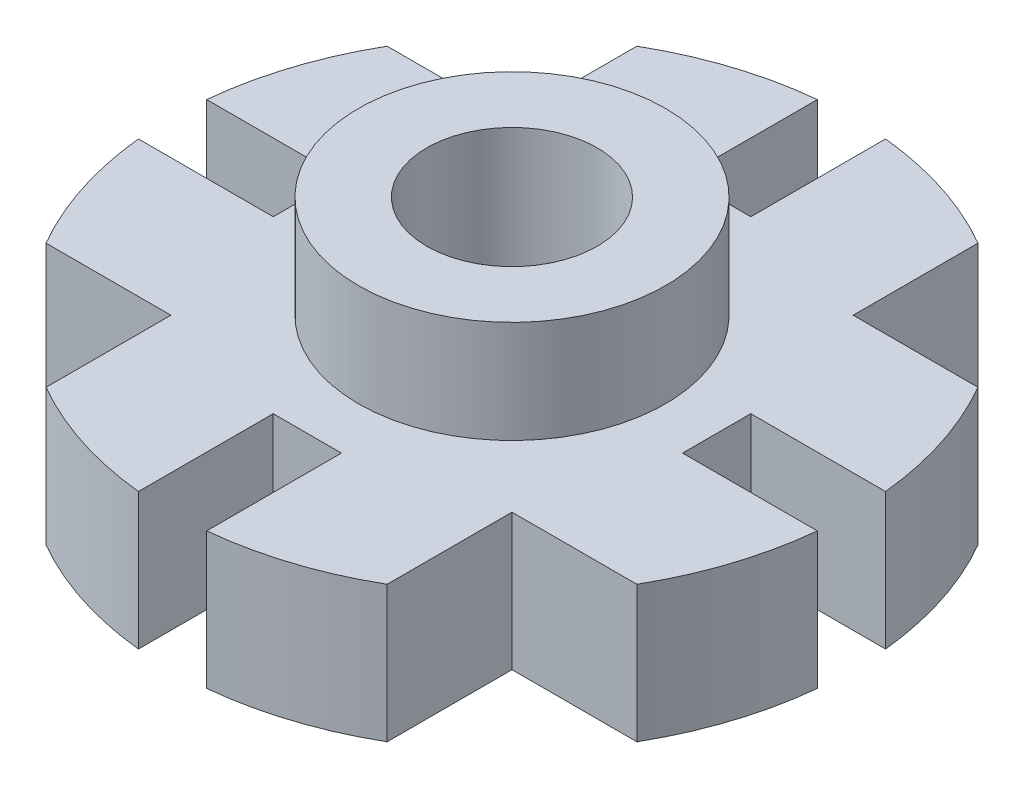
SolidWorks part; units mm, degrees
ref_plane "Front Plane" through (0, 0, 0) normal (0, 0, 1) x (1, 0, 0)
ref_plane "Top Plane" through (0, 0, 0) normal (0, 1, 0) x (1, 0, 0)
ref_plane "Right Plane" through (0, 0, 0) normal (1, 0, 0) x (0, 0, -1)
sketch "Sketch5" plane through (0, 0, 0) normal (0, 1, 0) x (1, 0, 0)
  circle A0 centre (20.7089, 32.9412) radius 63.5
extrude "Boss-Extrude4" add sketch "Sketch5" along normal blind 25.4
sketch "Sketch6" plane through (0, 25.4, 0) normal (0, 1, 0) x (1, 0, 0)
  line L0 (20.7089, 32.9412) -> (-133.4711, 32.9412)
  line L1 (14.3589, 71.0412) -> (27.0589, 71.0412)
  line L2 (14.3589, 71.0412) -> (14.3589, 96.4412)
  line L3 (14.3589, 96.4412) -> (27.0589, 96.4412)
  line L4 (27.0589, 71.0412) -> (27.0589, 96.4412)
  line L5 (14.3589, -5.1588) -> (27.0589, -5.1588)
  line L6 (14.3589, -5.1588) -> (14.3589, -30.5588)
  line L7 (14.3589, -30.5588) -> (27.0589, -30.5588)
  line L8 (27.0589, -5.1588) -> (27.0589, -30.5588)
  line L9 (20.7089, 32.9412) -> (171.0795, 32.9412)
  line L10 (20.7089, 32.9412) -> (20.7089, 112.5953)
  line L11 (20.7089, 32.9412) -> (20.7089, -53.8897)
  line L13 (-42.7911, 39.2912) -> (-17.3911, 39.2912)
  line L14 (-42.7911, 39.2912) -> (-42.7911, 26.5912)
  line L15 (-42.7911, 26.5912) -> (-17.3911, 26.5912)
  line L16 (-17.3911, 39.2912) -> (-17.3911, 26.5912)
  line L17 (58.8089, 39.2912) -> (84.2089, 39.2912)
  line L18 (58.8089, 39.2912) -> (58.8089, 26.5912)
  line L19 (58.8089, 26.5912) -> (84.2089, 26.5912)
  line L20 (84.2089, 39.2912) -> (84.2089, 26.5912)
  circle A0 centre (20.7089, 32.9412) radius 63.5 construction
  circle M17 centre (20.7089, 32.9412) radius 63.5
  dimension "D1" = 12.7
  dimension "D2" = 12.7
  dimension "D3" = 76.2
  dimension "D4" = 6.35
  dimension "D5" = 6.35
  dimension "D6" = 38.1
  dimension "D7" = 63.5
  dimension "D8" = 63.5
  dimension "D9" = 12.7
  dimension "D10" = 6.35
  dimension "D11" = 12.7
  dimension "D12" = 6.35
  dimension "D13" = 38.1
  dimension "D14" = 76.2
  dimension "D15" = 63.5
  dimension "D16" = 63.5
extrude "Cut-Extrude1" cut sketch "Sketch6" against normal blind 25.4 contours L18 L19 L9 M17 | L17 L18 L9 M17 | L10 L1 L4 M17 | L1 L10 L2 M17 | L16 L13 L0 M17 | L16 L0 L15 M17 | L11 L5 L6 M17 | L5 L11 L8 M17
sketch "Sketch7" plane through (0, 25.4, 0) normal (0, 1, 0) x (1, 0, 0)
  line L0 (58.8089, 26.5912) -> (83.8906, 26.5912) construction
  line L1 (52.4589, 1.1912) -> (84.6666, 1.1912)
  line L2 (52.4589, 1.1912) -> (52.4589, -27.8437)
  line L3 (52.4589, -27.8437) -> (84.6666, -27.8437)
  line L4 (84.6666, 1.1912) -> (84.6666, -27.8437)
  line L5 (27.0589, -5.1588) -> (27.0589, -30.2405) construction
  line L6 (14.3589, -5.1588) -> (14.3589, -30.2405) construction
  line L7 (-11.0411, 1.1912) -> (-51.882, 1.1912)
  line L8 (-11.0411, 1.1912) -> (-11.0411, -49.6088)
  line L9 (-11.0411, -49.6088) -> (-51.882, -49.6088)
  line L10 (-51.882, 1.1912) -> (-51.882, -49.6088)
  line L11 (-11.0411, 64.6912) -> (-61.8411, 64.6912)
  line L12 (-11.0411, 64.6912) -> (-11.0411, 110.8188)
  line L13 (-11.0411, 110.8188) -> (-61.8411, 110.8188)
  line L14 (-61.8411, 64.6912) -> (-61.8411, 110.8188)
  line L15 (52.4589, 64.6912) -> (104.7991, 64.6912)
  line L16 (52.4589, 64.6912) -> (52.4589, 112.513)
  line L17 (52.4589, 112.513) -> (104.7991, 112.513)
  line L18 (104.7991, 64.6912) -> (104.7991, 112.513)
  line L19 (-42.4728, 26.5912) -> (-17.3911, 26.5912) construction
  line L20 (-42.4728, 39.2912) -> (-17.3911, 39.2912) construction
  line L21 (14.3589, 71.0412) -> (14.3589, 96.1229) construction
  line L22 (27.0589, 71.0412) -> (27.0589, 96.1229) construction
  line L23 (58.8089, 39.2912) -> (83.8906, 39.2912) construction
  dimension "D1" = 25.4
  dimension "D2" = 25.4
  dimension "D3" = 25.4
  dimension "D4" = 25.4
  dimension "D5" = 50.8
  dimension "D6" = 50.8
  dimension "D7" = 25.4
  dimension "D8" = 25.4
  dimension "D9" = 25.4
  dimension "D10" = 25.4
extrude "Cut-Extrude2" cut sketch "Sketch7" against normal blind 25.4
sketch "Sketch8" plane through (0, 25.4, 0) normal (0, 1, 0) x (1, 0, 0)
  line L0 (14.3589, 71.0412) -> (27.0589, 71.0412) construction
  line L1 (58.8089, 39.2912) -> (58.8089, 26.5912) construction
  circle A0 centre (20.7089, 32.9412) radius 28.575
  dimension "D1" = 57.15
  dimension "D2" = 38.1
  dimension "D3" = 38.1
extrude "Boss-Extrude5" add sketch "Sketch8" along normal blind 19.05
sketch "Sketch12" plane through (0, 44.45, 0) normal (0, 1, 0) x (1, 0, 0)
  circle A0 centre (20.7089, 32.9412) radius 15.875
  circle A1 centre (20.7089, 32.9412) radius 28.575 construction
  dimension "D1" = 31.75
  dimension "D2" = 0
extrude "Cut-Extrude3" cut sketch "Sketch12" against normal blind 72.644
